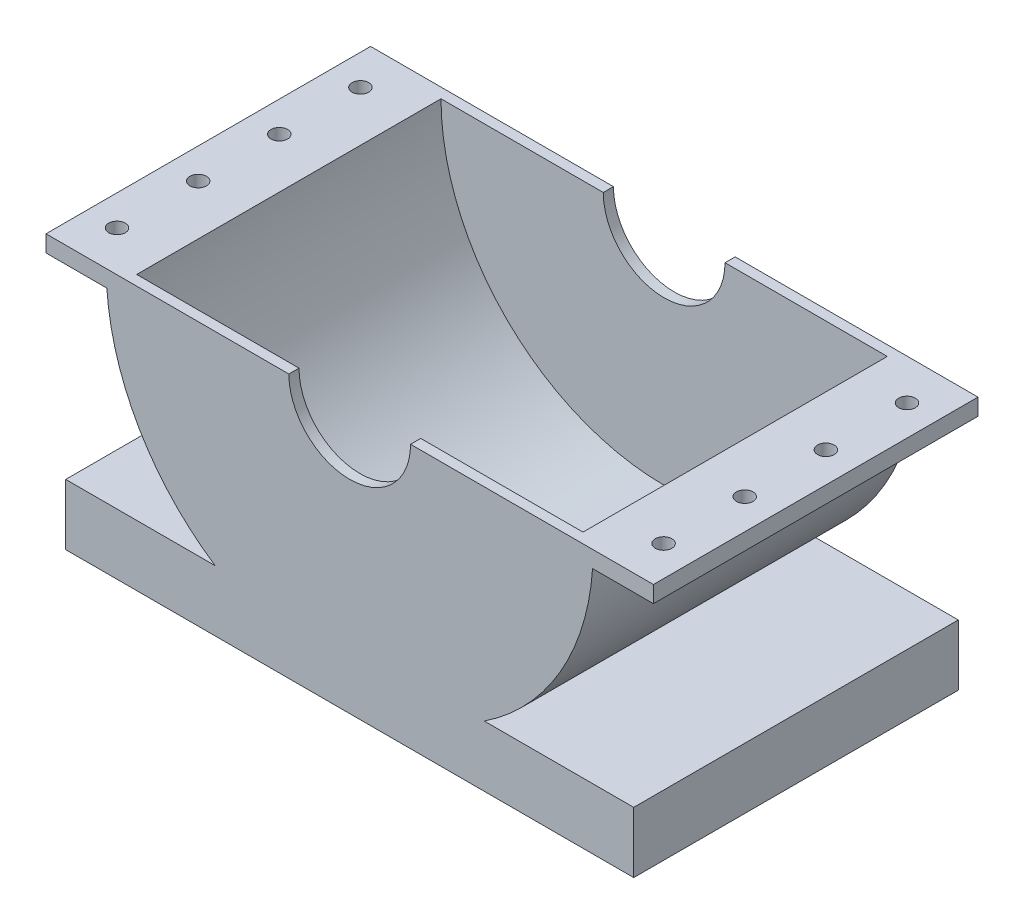
SolidWorks part; units mm, degrees
ref_plane "Front Plane" through (0, 0, 0) normal (0, 0, 1) x (1, 0, 0)
ref_plane "Top Plane" through (0, 0, 0) normal (0, 1, 0) x (1, 0, 0)
ref_plane "Right Plane" through (0, 0, 0) normal (1, 0, 0) x (0, 0, -1)
sketch "Sketch1" plane through (0, 0, 0) normal (0, 0, 1) x (1, 0, 0)
  line L0 (0, 0) -> (-50000, 0) construction
  line L1 (-1.5, 0) -> (-7.486, 0)
  line L2 (-7.486, 0) -> (-7.486, -0.41)
  line L3 (-7.486, -0.41) -> (-5.986, -0.41)
  line L4 (0, 6.8231) -> (0, -8.8338) construction
  line L5 (7.486, -0.41) -> (5.986, -0.41)
  line L6 (7.486, 0) -> (7.486, -0.41)
  line L7 (1.5, 0) -> (7.486, 0)
  line L8 (-7, -6.5) -> (7, -6.5)
  line L9 (-7, -6.5) -> (-7, -5)
  line L10 (-7, -5) -> (-3.3166, -5)
  line L11 (7, -6.5) -> (7, -5)
  line L12 (7, -5) -> (3.3166, -5)
  arc A0 (-5.986, -0.41) -> (-3.3166, -5) centre (0, 0) ccw
  arc A1 (-1.5, 0) -> (1.5, 0) centre (0, 0) ccw
  arc A2 (3.3166, -5) -> (5.986, -0.41) centre (0, 0) ccw
  point P17 (0, -6.5)
  dimension "D1" = 12
  dimension "D2" = 3
  dimension "D3" = 0.41
  dimension "D4" = 1.5
  dimension "D5" = 14
  dimension "D6" = 6.5
  dimension "D7" = 1.5
extrude "Boss-Extrude1" add sketch "Sketch1" along normal mid plane 8
sketch "Sketch2" plane through (0, 0, 0) normal (0, 0, 1) x (1, 0, 0)
  circle A0 centre (0, 0) radius 5.5
  dimension "D1" = 11
extrude "Cut-Extrude1" cut sketch "Sketch2" against normal blind 3.75 and the other way blind 3.75
hole_wizard "Ø1.0mm Dowel Hole1" positions "Sketch3" profile "Sketch4" hole size "Ø1.0" standard "ISO"
sketch "Sketch3" plane through (0, 0, 0) normal (0, 1, 0) x (1, 0, 0)
  line L0 (7.486, -4) -> (7.486, 4) construction
  line L1 (7.486, 4) -> (1.5, 4) construction
  point P0 (6.736, 3)
  dimension "D1" = 0.75
  dimension "D2" = 1
sketch "Sketch4" plane through (6.736, 0, -3) normal (1, 0, 0) x (0, 0, 1)
  line L0 (0, 0) -> (0, 6.5)
  line L1 (0, 6.5) -> (0.205, 6.5)
  line L2 (0.205, 6.5) -> (0.205, 0)
  line L5 (0.205, 0) -> (0, 0)
  line L11 (0, -6.35) -> (0, 107.95) construction
  dimension "Thru Hole Dia." = 0.41
  dimension "Thru Hole Depth" = 6.5
pattern_linear "LPattern1" count 4 spacing 2 along (0, 0, 1) of "Ø1.0mm Dowel Hole1"
mirror "Mirror1" about plane through (0, 0, 0) normal (1, 0, 0) of "LPattern1", "Ø1.0mm Dowel Hole1"
